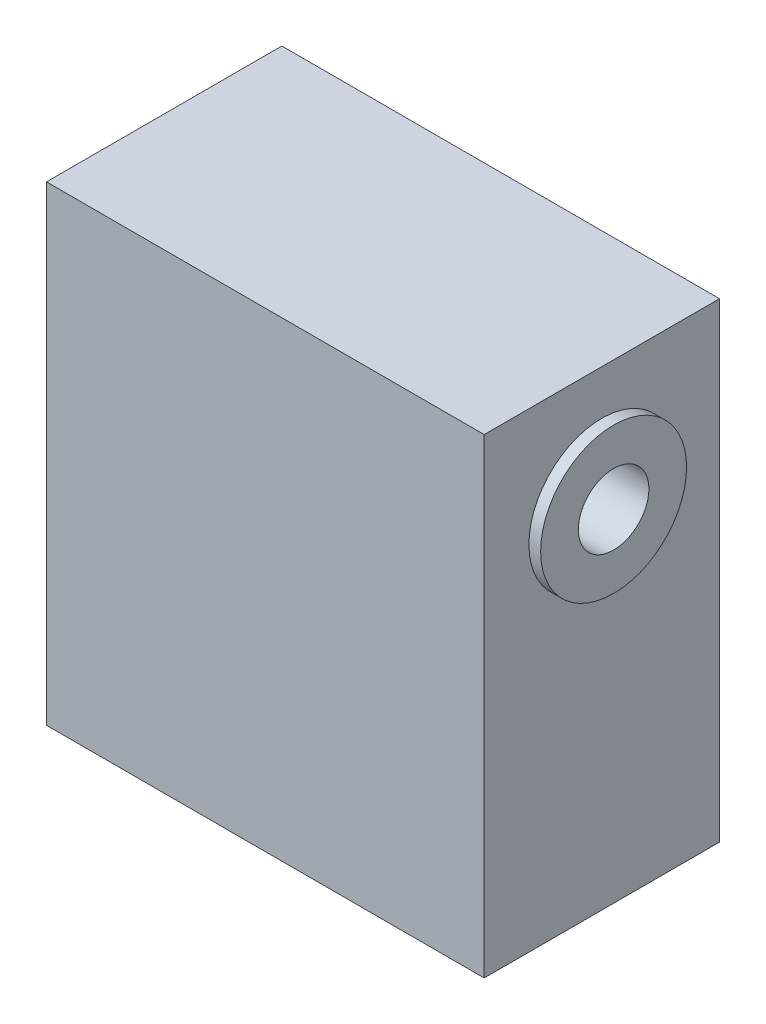
SolidWorks part; units mm, degrees
ref_plane "Front Plane" through (0, 0, 0) normal (0, 0, 1) x (1, 0, 0)
ref_plane "Top Plane" through (0, 0, 0) normal (0, 1, 0) x (1, 0, 0)
ref_plane "Right Plane" through (0, 0, 0) normal (1, 0, 0) x (0, 0, -1)
sketch "Sketch1" plane through (0, 0, 0) normal (0, 1, 0) x (1, 0, 0)
  line L1 (0, 0) -> (-37.2, 0)
  line L2 (0, 0) -> (0, 20)
  line L3 (0, 20) -> (-37.2, 20)
  line L4 (-37.2, 0) -> (-37.2, 20)
  dimension "D1" = 20
  dimension "D2" = 37.2
extrude "Boss-Extrude1" add sketch "Sketch1" along normal blind 40
sketch "Sketch2" plane through (0, 0, 0) normal (1, 0, 0) x (0, 0, -1)
  line L0 (0, 40) -> (20, 40) construction
  line L1 (20, 40) -> (20, 0) construction
  circle A0 centre (10, 30) radius 6.2
  dimension "D1" = 12.4
  dimension "D2" = 10
  dimension "D3" = 10
extrude "Boss-Extrude2" add sketch "Sketch2" along normal blind 1
sketch "Sketch3" plane through (1, 0, 0) normal (1, 0, 0) x (0, 0, -1)
  circle A0 centre (10, 30) radius 3
  dimension "D1" = 6
extrude "Cut-Extrude1" cut sketch "Sketch3" against normal blind 10
